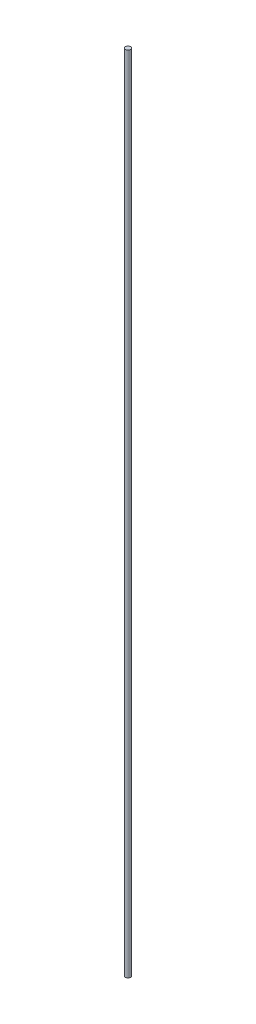
SolidWorks part; units mm, degrees
ref_plane "Front Plane" through (0, 0, 0) normal (0, 0, 1) x (1, 0, 0)
ref_plane "Top Plane" through (0, 0, 0) normal (0, 1, 0) x (1, 0, 0)
ref_plane "Right Plane" through (0, 0, 0) normal (1, 0, 0) x (0, 0, -1)
sketch "Sketch1" plane through (0, 0, 0) normal (0, 1, 0) x (1, 0, 0)
  circle A0 centre (0, 0) radius 3.175
  dimension "D1" = 6.35
extrude "Boss-Extrude1" add sketch "Sketch1" along normal mid plane 1000
